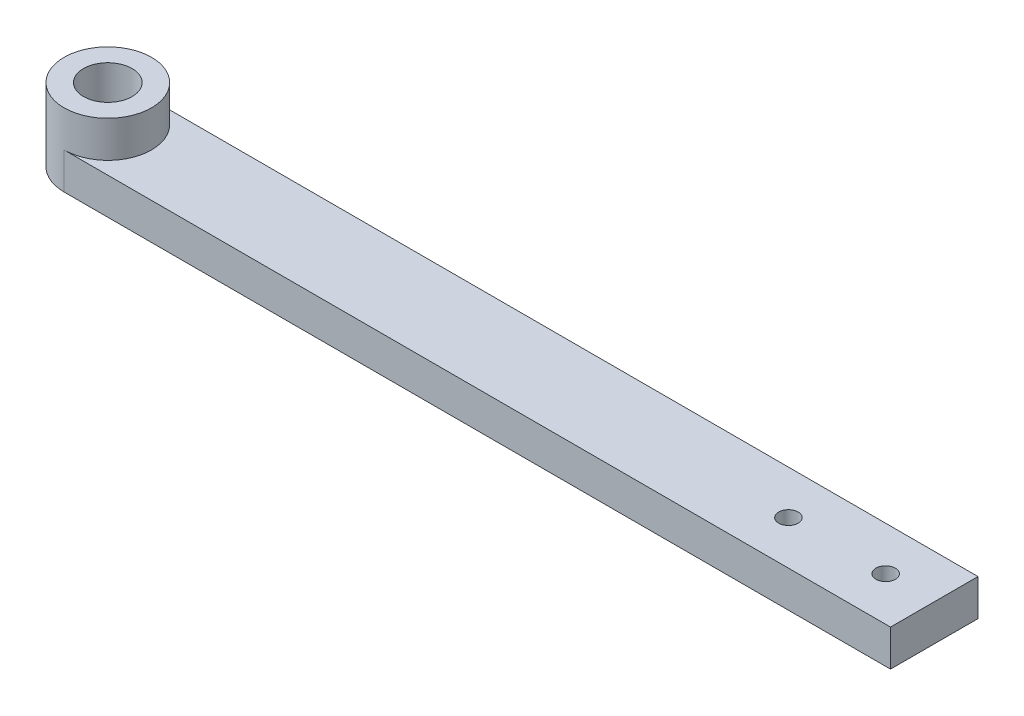
SolidWorks part; units mm, degrees
ref_plane "Front Plane" through (0, 0, 0) normal (0, 0, 1) x (1, 0, 0)
ref_plane "Top Plane" through (0, 0, 0) normal (0, 1, 0) x (1, 0, 0)
ref_plane "Right Plane" through (0, 0, 0) normal (1, 0, 0) x (0, 0, -1)
sketch "Sketch1" plane through (0, 0, 0) normal (0, 1, 0) x (1, 0, 0)
  line L0 (0, 9) -> (170, 9)
  line L1 (170, 9) -> (170, -9)
  line L2 (170, -9) -> (0, -9)
  arc A0 (0, 9) -> (0, -9) centre (0, 0) ccw
  dimension "D1" = 18
  dimension "D2" = 170
  dimension "D3" = 9
extrude "Boss-Extrude1" add sketch "Sketch1" along normal blind 7.5
sketch "Sketch2" plane through (0, 7.5, 0) normal (0, 1, 0) x (1, 0, 0)
  line L0 (170, -9) -> (170, 9) construction
  circle A0 centre (0, 0) radius 5
  circle A1 centre (160, 0) radius 2
  circle A2 centre (140, 0) radius 2
  dimension "D1" = 4
  dimension "D4" = 10
  dimension "D2" = 10
  dimension "D3" = 20
extrude "Cut-Extrude1" cut sketch "Sketch2" against normal through all
sketch "Sketch3" plane through (0, 7.5, 0) normal (0, 1, 0) x (1, 0, 0)
  circle A0 centre (0, 0) radius 9
  dimension "D1" = 18
extrude "Boss-Extrude2" add sketch "Sketch3" along normal blind 7.5
sketch "Sketch4" plane through (0, 7.5, 0) normal (0, -1, 0) x (1, 0, 0)
  circle A0 centre (0, 0) radius 5
  dimension "D1" = 10
extrude "Cut-Extrude2" cut sketch "Sketch4" against normal through all
